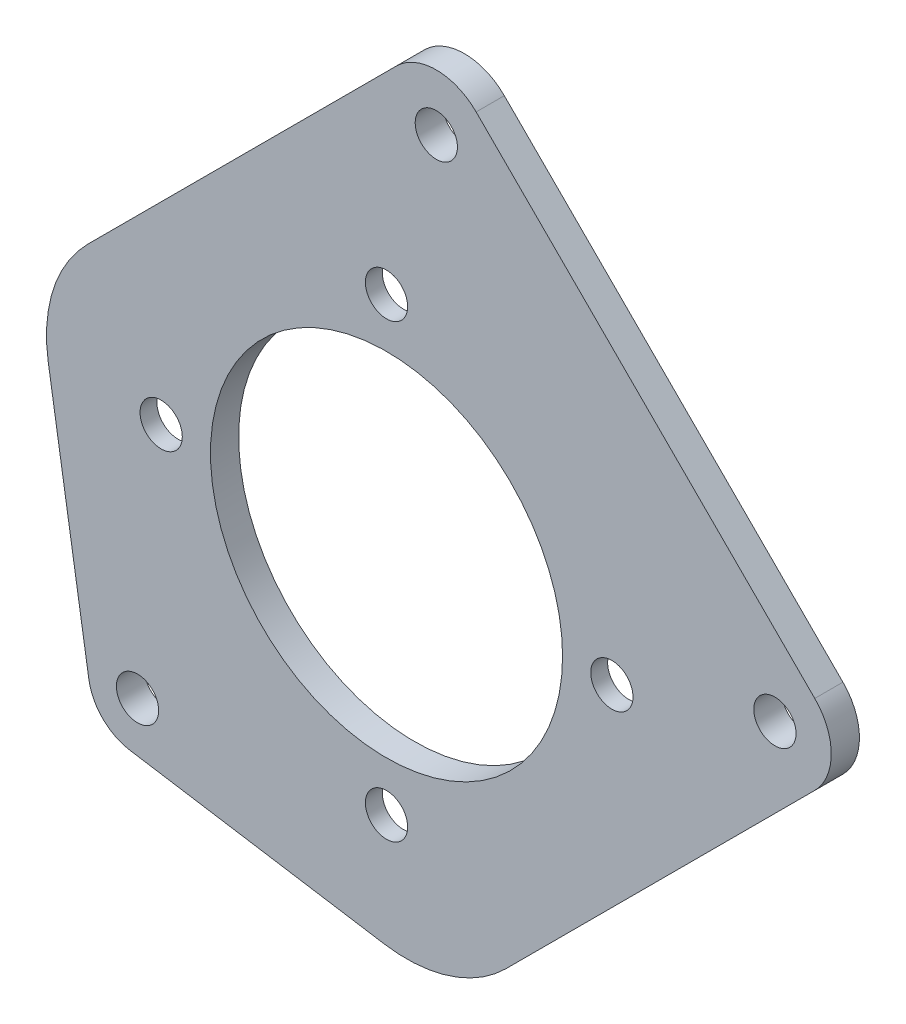
SolidWorks part; units mm, degrees
ref_plane "Přední rovina" through (0, 0, 0) normal (0, 0, 1) x (1, 0, 0)
ref_plane "Horní rovina" through (0, 0, 0) normal (0, 1, 0) x (1, 0, 0)
ref_plane "Pravá rovina" through (0, 0, 0) normal (1, 0, 0) x (0, 0, -1)
sketch "Skica1" plane through (0, 0, 0) normal (0, 0, 1) x (1, 0, 0)
  line L0 (0, 0) -> (-15.4246, 0) construction
  line L1 (0, 0) -> (-17.6777, -17.6777) construction
  line L2 (6.364, 30.4056) -> (30.4056, 6.364)
  line L3 (12.4013, -12.4013) -> (0, 0) construction
  line L4 (-21.2132, 8.4853) -> (0.7071, 30.4056)
  line L5 (-24.0172, -0.1617) -> (-21.1339, -18.2292)
  line L6 (8.4853, -21.2132) -> (30.4056, 0.7071)
  line L7 (-0.1617, -24.0172) -> (-18.2292, -21.1339)
  line L8 (3.5355, 27.5772) -> (-17.6777, -17.6777) construction
  circle A0 centre (0, 0) radius 12.5
  circle A1 centre (0, 16) radius 1.5
  circle A2 centre (16, 0) radius 1.5
  circle A3 centre (0, -16) radius 1.5
  circle A4 centre (-16, 0) radius 1.5
  circle A5 centre (-17.6777, -17.6777) radius 1.5
  circle A6 centre (27.5772, 3.5355) radius 1.5
  circle A7 centre (3.5355, 27.5772) radius 1.5
  arc A8 (6.364, 30.4056) -> (0.7071, 30.4056) centre (3.5355, 27.5772) ccw
  arc A9 (30.4056, 0.7071) -> (30.4056, 6.364) centre (27.5772, 3.5355) ccw
  arc A10 (-21.1339, -18.2292) -> (-18.2292, -21.1339) centre (-17.6777, -17.6777) ccw
  circle A11 centre (-17.6777, -17.6777) radius 49.98 construction
  arc A12 (-21.2132, 8.4853) -> (-24.0172, -0.1617) centre (-14.1421, 1.4142) ccw
  arc A13 (8.4853, -21.2132) -> (-0.1617, -24.0172) centre (1.4142, -14.1421) cw
  arc A14 (7.8822, 27.124) -> (0.4066, 30.6282) centre (-17.6777, -17.6777) ccw construction
  arc A15 (6.2965, 24.3445) -> (-0.7153, 27.6313) centre (-17.6777, -17.6777) ccw construction
  arc A16 (0.4066, 30.6282) -> (-0.7153, 27.6313) centre (-0.1543, 29.1297) ccw construction
  arc A17 (7.8822, 27.124) -> (6.2965, 24.3445) centre (7.0893, 25.7343) cw construction
  circle A18 centre (-17.6777, -17.6777) radius 48.38 construction
  circle A19 centre (-17.6777, -17.6777) radius 51.58 construction
  arc A20 (27.124, 7.8822) -> (24.3445, 6.2965) centre (25.7343, 7.0893) ccw construction
  arc A21 (24.3445, 6.2965) -> (27.6313, -0.7153) centre (-17.6777, -17.6777) cw construction
  arc A22 (30.6282, 0.4066) -> (27.6313, -0.7153) centre (29.1297, -0.1543) cw construction
  arc A23 (27.124, 7.8822) -> (30.6282, 0.4066) centre (-17.6777, -17.6777) cw construction
  point P15 (0, 0)
  dimension "D1" = 25
  dimension "D2" = 3
  dimension "D3" = 32
  dimension "D7" = 3
  dimension "D8" = 22
  dimension "D10" = 10
  dimension "D11" = 8
  dimension "D12" = 7
  dimension "D15" = 1.6
  dimension "D16" = 8
  dimension "D5" = 25
  dimension "D6" = 45
  dimension "D9" = 34
  dimension "D13" = 35
  dimension "D14" = 1.6
  dimension "D4" = 4
extrude "Přidat vysunutím1" add sketch "Skica1" along normal blind 2
chamfer "Zkosení1" distance 0.8 angle 60 4 edges at (1.5, 16, 0) (17.5, 0, 0) (1.5, -16, 0) (-14.5, 0, 0)
move or copy body "Tělo-Přesunout/kopírovat1" [suppressed] bodies to move or copy 101
